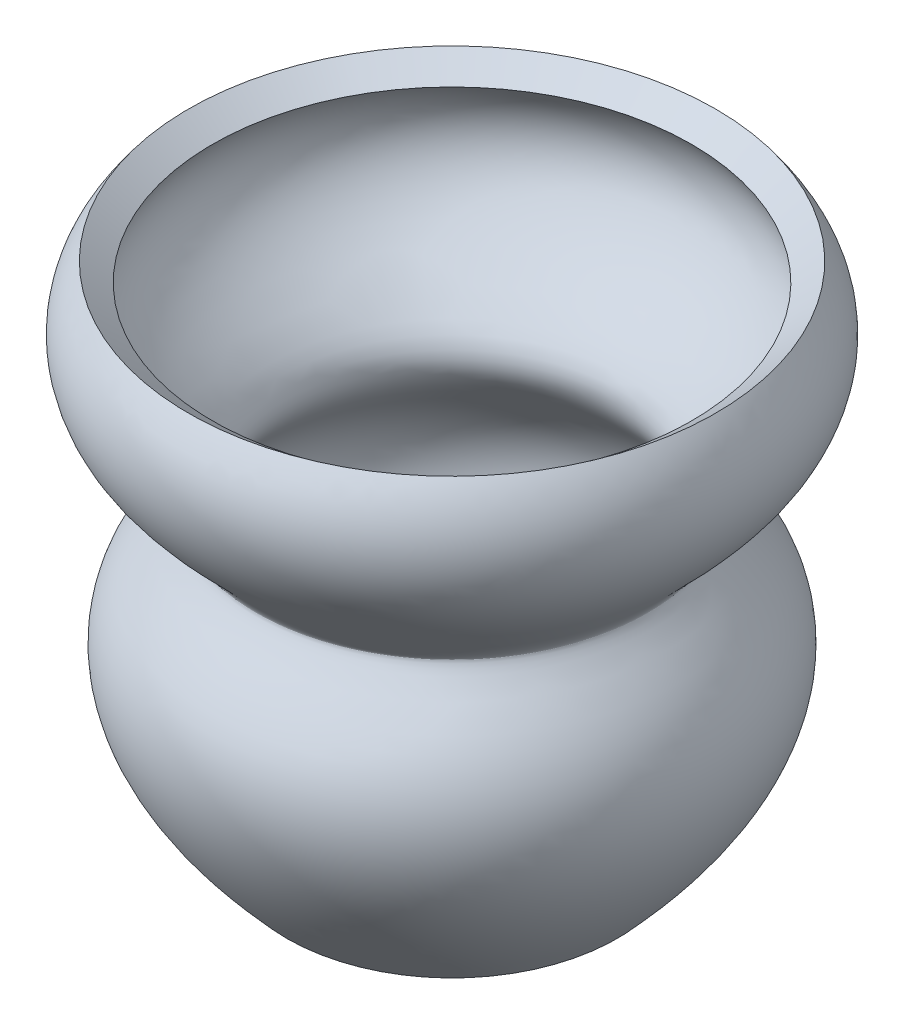
SolidWorks part; units mm, degrees
ref_plane "Front Plane" through (0, 0, 0) normal (0, 0, 1) x (1, 0, 0)
ref_plane "Top Plane" through (0, 0, 0) normal (0, 1, 0) x (1, 0, 0)
ref_plane "Right Plane" through (0, 0, 0) normal (1, 0, 0) x (0, 0, -1)
sketch "Sketch1" plane through (0, 0, 0) normal (0, 0, 1) x (1, 0, 0)
  line L0 (0, 0) -> (25, 0)
  line L1 (0, 0) -> (0, 74.9845) construction
  line L2 (0, 31.7983) -> (35, 31.7983) construction
  line L3 (0, 46.6998) -> (28, 46.6998) construction
  line L4 (0, 74.9845) -> (39.4788, 74.9845) construction
  line L5 (0, -5) -> (27.2348, -5)
  line L6 (39.4788, 74.9845) -> (43.4281, 78.0509)
  line L7 (0, 0) -> (0, -5)
  spline S0 degree 3 poles (25, 0) (54.1229, 32.5336) (2.7633, 37.6839) (48.9621, 62.7707) (39.4788, 74.9845) knots 0 0 0 0 0.623313 1 1 1 1
  spline S1 degree 1 poles (27.2348, -5) (43.4281, 78.0509) knots 0 0 1 1 construction
  spline S2 degree 3 poles (27.2348, -5) (27.6037, -4.5879) (28.1542, -3.9724) (28.8998, -3.1411) (30.0438, -1.8477) (32.3379, 0.8547) (35.3479, 4.8072) (38.158, 9.2258) (40.2402, 13.3858) (41.6369, 17.3322) (42.63, 22.3446) (42.2681, 28.1163) (39.9273, 33.6971) (36.9023, 37.8722) (34.5844, 40.5186) (33.2353, 42.1974) (32.563, 43.1904) (32.2719, 43.825) (32.2566, 44.0018) (32.2532, 43.9361) (32.2885, 44.1372) (32.5752, 44.6359) (33.1256, 45.4061) (34.2283, 46.682) (36.0299, 48.5308) (38.8226, 51.3299) (42.6308, 55.4012) (45.9049, 60.4949) (47.3046, 65.5526) (47.3302, 69.0654) (46.7146, 71.914) (45.934, 74.0255) (44.8567, 76.0686) (43.9219, 77.415) (43.4281, 78.0509) knots -0.010634 -0.010634 -0.010634 -0.010634 -0.002739 0.001209 0.005157 0.020948 0.05253 0.084113 0.115695 0.147277 0.17886 0.242024 0.305189 0.368354 0.431518 0.463101 0.494683 0.526265 0.557848 0.58943 0.621012 0.636803 0.652595 0.684177 0.715759 0.747341 0.810506 0.873671 0.905253 0.936835 0.952627 0.968418 0.984209 1 1 1 1
  point P14 (39.4788, 77.9994)
  point P15 (0, 0)
  point P16 (0, 0)
  dimension "D7" = 87.2729
  dimension "D1" = 25
  dimension "D2" = 35
  dimension "D3" = 28
  dimension "D4" = 39.4788
  dimension "D6" = 5
  dimension "D5" = 5
revolve "Revolve2" add sketch "Sketch1" angle 360 about L1
